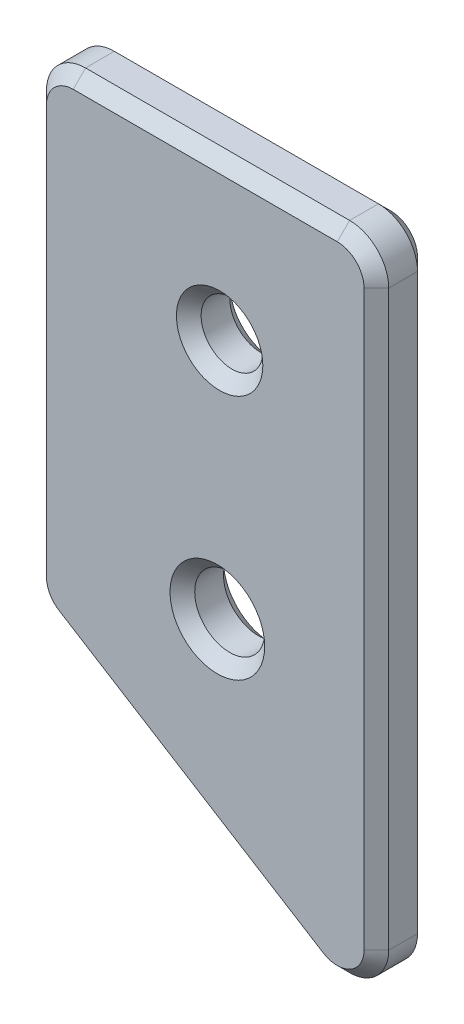
SolidWorks part; units mm, degrees
ref_plane "Front Plane" through (0, 0, 0) normal (0, 0, 1) x (1, 0, 0)
ref_plane "Top Plane" through (0, 0, 0) normal (0, 1, 0) x (1, 0, 0)
ref_plane "Right Plane" through (0, 0, 0) normal (1, 0, 0) x (0, 0, -1)
sketch "Sketch1" plane through (0, 0, 0) normal (0, 0, 1) x (1, 0, 0)
  line L3 (435.95, -297.537) -> (-11.4581, -19.05) construction
  line L9 (53.3811, -59.4088) -> (-11.4581, -19.05)
  line L11 (19.05, 19.05) -> (-13.7235, 19.05)
  line L12 (-19.05, -5.7912) -> (-19.05, 5.7912)
  line L13 (60.6412, -19.05) -> (60.6412, 14.3)
  line L14 (60.6412, -19.05) -> (60.6412, -55.3762)
  line L24 (19.05, 19.05) -> (19.05, 17.3228)
  line L25 (19.05, 17.3228) -> (704.05, 17.3228)
  line L26 (704.05, 17.3228) -> (704.05, 19.05)
  line L27 (704.05, 19.05) -> (19.05, 19.05)
  line L31 (55.8912, 19.05) -> (19.05, 19.05)
  line L44 (19.05, -6.9643) -> (19.05, -5.7912)
  line L45 (17.3228, -4.064) -> (16.7132, -4.064)
  line L46 (14.986, -5.7912) -> (14.986, -8.9963)
  line L47 (12.7826, -9.909) -> (7.8889, -5.0152)
  line L48 (6.985, -2.833) -> (6.985, 2.833)
  line L49 (7.8889, 5.0152) -> (12.7826, 9.909)
  line L50 (14.986, 8.9963) -> (14.986, 5.7912)
  line L51 (16.7132, 4.064) -> (17.3228, 4.064)
  line L52 (19.05, 5.7912) -> (19.05, 6.9643)
  line L53 (19.05, 8.9963) -> (19.05, 13.7235)
  line L54 (13.7235, 19.05) -> (8.9963, 19.05)
  line L55 (6.9643, 19.05) -> (5.7912, 19.05)
  line L56 (4.064, 17.3228) -> (4.064, 16.7132)
  line L57 (5.7912, 14.986) -> (8.9963, 14.986)
  line L58 (9.909, 12.7826) -> (5.0152, 7.8889)
  line L59 (2.833, 6.985) -> (-2.833, 6.985)
  line L60 (-5.0152, 7.8889) -> (-9.909, 12.7826)
  line L61 (-8.9963, 14.986) -> (-5.7912, 14.986)
  line L62 (-4.064, 16.7132) -> (-4.064, 17.3228)
  line L63 (-5.7912, 19.05) -> (-6.9643, 19.05)
  line L64 (-8.9963, 19.05) -> (-13.7235, 19.05)
  line L65 (-19.05, 13.7235) -> (-19.05, 8.9963)
  line L66 (-19.05, 6.9643) -> (-19.05, 5.7912)
  line L67 (-17.3228, 4.064) -> (-16.7132, 4.064)
  line L68 (-14.986, 5.7912) -> (-14.986, 8.9963)
  line L69 (-12.7826, 9.909) -> (-7.8889, 5.0152)
  line L70 (-6.985, 2.833) -> (-6.985, -2.833)
  line L71 (-7.8889, -5.0152) -> (-12.7826, -9.909)
  line L72 (-14.986, -8.9963) -> (-14.986, -5.7912)
  line L73 (-16.7132, -4.064) -> (-17.3228, -4.064)
  line L74 (-19.05, -5.7912) -> (-19.05, -6.9643)
  line L75 (-19.05, -8.9963) -> (-19.05, -13.7235)
  line L76 (-13.7235, -19.05) -> (-8.9963, -19.05)
  line L77 (-6.9643, -19.05) -> (-5.7912, -19.05)
  line L78 (-4.064, -17.3228) -> (-4.064, -16.7132)
  line L79 (-5.7912, -14.986) -> (-8.9963, -14.986)
  line L80 (-9.909, -12.7826) -> (-5.0152, -7.8889)
  line L81 (-2.833, -6.985) -> (2.833, -6.985)
  line L82 (5.0152, -7.8889) -> (9.909, -12.7826)
  line L83 (8.9963, -14.986) -> (5.7912, -14.986)
  line L84 (4.064, -16.7132) -> (4.064, -17.3228)
  line L85 (5.7912, -19.05) -> (6.9643, -19.05)
  line L86 (8.9963, -19.05) -> (13.7235, -19.05)
  line L87 (19.05, -13.7235) -> (19.05, -8.9963)
  line L108 (-8.9963, 19.05) -> (-13.7235, 19.05)
  line L109 (-19.05, 13.7235) -> (-19.05, 8.9963)
  line L110 (-19.05, 6.9643) -> (-19.05, 5.7912)
  line L118 (-19.05, -5.7912) -> (-19.05, -6.9643)
  line L119 (-19.05, -8.9963) -> (-19.05, -13.7235)
  line L120 (-13.7235, -19.05) -> (-11.4581, -19.05)
  circle A3 centre (41.315, -29.4594) radius 4.25
  circle A4 centre (41.5912, 0) radius 3.75
  arc A5 (55.8912, 19.05) -> (60.6412, 14.3) centre (55.8912, 14.3) cw
  arc A6 (60.6412, -55.3762) -> (53.3811, -59.4088) centre (55.8912, -55.3762) cw
  circle A7 centre (0, 0) radius 4.5
  arc A52 (19.05, -6.9643) -> (19.05, -8.9963) centre (19.05, -7.9803) ccw
  arc A53 (19.05, -5.7912) -> (17.3228, -4.064) centre (17.3228, -5.7912) ccw
  arc A54 (16.7132, -4.064) -> (14.986, -5.7912) centre (16.7132, -5.7912) ccw
  arc A55 (12.7826, -9.909) -> (14.986, -8.9963) centre (13.6953, -8.9963) ccw
  arc A56 (6.985, -2.833) -> (7.8889, -5.0152) centre (10.0711, -2.833) ccw
  arc A57 (7.8889, 5.0152) -> (6.985, 2.833) centre (10.0711, 2.833) ccw
  arc A58 (14.986, 8.9963) -> (12.7826, 9.909) centre (13.6953, 8.9963) ccw
  arc A59 (14.986, 5.7912) -> (16.7132, 4.064) centre (16.7132, 5.7912) ccw
  arc A60 (17.3228, 4.064) -> (19.05, 5.7912) centre (17.3228, 5.7912) ccw
  arc A61 (19.05, 8.9963) -> (19.05, 6.9643) centre (19.05, 7.9803) ccw
  arc A62 (18.8293, 15.7312) -> (19.05, 13.7235) centre (19.05, 14.7395) ccw
  arc A63 (18.8293, 15.7312) -> (15.7312, 18.8293) centre (14.3002, 14.3002) ccw
  arc A64 (13.7235, 19.05) -> (15.7312, 18.8293) centre (14.7395, 19.05) ccw
  arc A65 (6.9643, 19.05) -> (8.9963, 19.05) centre (7.9803, 19.05) ccw
  arc A66 (5.7912, 19.05) -> (4.064, 17.3228) centre (5.7912, 17.3228) ccw
  arc A67 (4.064, 16.7132) -> (5.7912, 14.986) centre (5.7912, 16.7132) ccw
  arc A68 (9.909, 12.7826) -> (8.9963, 14.986) centre (8.9963, 13.6953) ccw
  arc A69 (2.833, 6.985) -> (5.0152, 7.8889) centre (2.833, 10.0711) ccw
  arc A70 (-5.0152, 7.8889) -> (-2.833, 6.985) centre (-2.833, 10.0711) ccw
  arc A71 (-8.9963, 14.986) -> (-9.909, 12.7826) centre (-8.9963, 13.6953) ccw
  arc A72 (-5.7912, 14.986) -> (-4.064, 16.7132) centre (-5.7912, 16.7132) ccw
  arc A73 (-4.064, 17.3228) -> (-5.7912, 19.05) centre (-5.7912, 17.3228) ccw
  arc A74 (-8.9963, 19.05) -> (-6.9643, 19.05) centre (-7.9803, 19.05) ccw
  arc A75 (-15.7312, 18.8293) -> (-13.7235, 19.05) centre (-14.7395, 19.05) ccw
  arc A76 (-15.7312, 18.8293) -> (-18.8293, 15.7312) centre (-14.3002, 14.3002) ccw
  arc A77 (-19.05, 13.7235) -> (-18.8293, 15.7312) centre (-19.05, 14.7395) ccw
  arc A78 (-19.05, 6.9643) -> (-19.05, 8.9963) centre (-19.05, 7.9803) ccw
  arc A79 (-19.05, 5.7912) -> (-17.3228, 4.064) centre (-17.3228, 5.7912) ccw
  arc A80 (-16.7132, 4.064) -> (-14.986, 5.7912) centre (-16.7132, 5.7912) ccw
  arc A81 (-12.7826, 9.909) -> (-14.986, 8.9963) centre (-13.6953, 8.9963) ccw
  arc A82 (-6.985, 2.833) -> (-7.8889, 5.0152) centre (-10.0711, 2.833) ccw
  arc A83 (-7.8889, -5.0152) -> (-6.985, -2.833) centre (-10.0711, -2.833) ccw
  arc A84 (-14.986, -8.9963) -> (-12.7826, -9.909) centre (-13.6953, -8.9963) ccw
  arc A85 (-14.986, -5.7912) -> (-16.7132, -4.064) centre (-16.7132, -5.7912) ccw
  arc A86 (-17.3228, -4.064) -> (-19.05, -5.7912) centre (-17.3228, -5.7912) ccw
  arc A87 (-19.05, -8.9963) -> (-19.05, -6.9643) centre (-19.05, -7.9803) ccw
  arc A88 (-18.8293, -15.7312) -> (-19.05, -13.7235) centre (-19.05, -14.7395) ccw
  arc A89 (-18.8293, -15.7312) -> (-15.7312, -18.8293) centre (-14.3002, -14.3002) ccw
  arc A90 (-13.7235, -19.05) -> (-15.7312, -18.8293) centre (-14.7395, -19.05) ccw
  arc A91 (-6.9643, -19.05) -> (-8.9963, -19.05) centre (-7.9803, -19.05) ccw
  arc A92 (-5.7912, -19.05) -> (-4.064, -17.3228) centre (-5.7912, -17.3228) ccw
  arc A93 (-4.064, -16.7132) -> (-5.7912, -14.986) centre (-5.7912, -16.7132) ccw
  arc A94 (-9.909, -12.7826) -> (-8.9963, -14.986) centre (-8.9963, -13.6953) ccw
  arc A95 (-2.833, -6.985) -> (-5.0152, -7.8889) centre (-2.833, -10.0711) ccw
  arc A96 (5.0152, -7.8889) -> (2.833, -6.985) centre (2.833, -10.0711) ccw
  arc A97 (8.9963, -14.986) -> (9.909, -12.7826) centre (8.9963, -13.6953) ccw
  arc A98 (5.7912, -14.986) -> (4.064, -16.7132) centre (5.7912, -16.7132) ccw
  arc A99 (4.064, -17.3228) -> (5.7912, -19.05) centre (5.7912, -17.3228) ccw
  arc A100 (8.9963, -19.05) -> (6.9643, -19.05) centre (7.9803, -19.05) ccw
  arc A101 (15.7312, -18.8293) -> (13.7235, -19.05) centre (14.7395, -19.05) ccw
  arc A102 (15.7312, -18.8293) -> (18.8293, -15.7312) centre (14.3002, -14.3002) ccw
  arc A103 (19.05, -13.7235) -> (18.8293, -15.7312) centre (19.05, -14.7395) ccw
  arc A127 (-15.7312, 18.8293) -> (-13.7235, 19.05) centre (-14.7395, 19.05) ccw
  arc A128 (-15.7312, 18.8293) -> (-18.8293, 15.7312) centre (-14.3002, 14.3002) ccw
  arc A129 (-19.05, 13.7235) -> (-18.8293, 15.7312) centre (-19.05, 14.7395) ccw
  arc A130 (-19.05, 6.9643) -> (-19.05, 8.9963) centre (-19.05, 7.9803) ccw
  arc A139 (-19.05, -8.9963) -> (-19.05, -6.9643) centre (-19.05, -7.9803) ccw
  arc A140 (-18.8293, -15.7312) -> (-19.05, -13.7235) centre (-19.05, -14.7395) ccw
  arc A141 (-18.8293, -15.7312) -> (-15.7312, -18.8293) centre (-14.3002, -14.3002) ccw
  arc A142 (-13.7235, -19.05) -> (-15.7312, -18.8293) centre (-14.7395, -19.05) ccw
  dimension "D4" = 4.75
  dimension "D1" = 0
  dimension "D3" = 0
extrude "Boss-Extrude1" add sketch "Sketch1" along normal blind 6.5
sketch "Sketch2" plane through (0, 0, 0) normal (0, 0, -1) x (-1, 0, 0)
  line L44 (-19.05, -5.7912) -> (-19.05, -6.9643)
  line L45 (-16.7132, -4.064) -> (-17.3228, -4.064)
  line L46 (-14.986, -8.9963) -> (-14.986, -5.7912)
  line L47 (-7.8889, -5.0152) -> (-12.7826, -9.909)
  line L48 (-6.985, 2.833) -> (-6.985, -2.833)
  line L49 (-12.7826, 9.909) -> (-7.8889, 5.0152)
  line L50 (-14.986, 5.7912) -> (-14.986, 8.9963)
  line L51 (-17.3228, 4.064) -> (-16.7132, 4.064)
  line L52 (-19.05, 6.9643) -> (-19.05, 5.7912)
  line L53 (-19.05, 13.7235) -> (-19.05, 8.9963)
  line L54 (-8.9963, 19.05) -> (-13.7235, 19.05)
  line L55 (-5.7912, 19.05) -> (-6.9643, 19.05)
  line L56 (-4.064, 16.7132) -> (-4.064, 17.3228)
  line L57 (-8.9963, 14.986) -> (-5.7912, 14.986)
  line L58 (-5.0152, 7.8889) -> (-9.909, 12.7826)
  line L59 (2.833, 6.985) -> (-2.833, 6.985)
  line L60 (9.909, 12.7826) -> (5.0152, 7.8889)
  line L61 (5.7912, 14.986) -> (8.9963, 14.986)
  line L62 (4.064, 17.3228) -> (4.064, 16.7132)
  line L63 (6.9643, 19.05) -> (5.7912, 19.05)
  line L64 (13.7235, 19.05) -> (8.9963, 19.05)
  line L65 (19.05, 8.9963) -> (19.05, 13.7235)
  line L66 (19.05, 5.7912) -> (19.05, 6.9643)
  line L67 (16.7132, 4.064) -> (17.3228, 4.064)
  line L68 (14.986, 8.9963) -> (14.986, 5.7912)
  line L69 (7.8889, 5.0152) -> (12.7826, 9.909)
  line L70 (6.985, -2.833) -> (6.985, 2.833)
  line L71 (12.7826, -9.909) -> (7.8889, -5.0152)
  line L72 (14.986, -5.7912) -> (14.986, -8.9963)
  line L73 (17.3228, -4.064) -> (16.7132, -4.064)
  line L74 (19.05, -6.9643) -> (19.05, -5.7912)
  line L75 (19.05, -13.7235) -> (19.05, -8.9963)
  line L76 (8.9963, -19.05) -> (13.7235, -19.05)
  line L77 (5.7912, -19.05) -> (6.9643, -19.05)
  line L78 (4.064, -16.7132) -> (4.064, -17.3228)
  line L79 (8.9963, -14.986) -> (5.7912, -14.986)
  line L80 (5.0152, -7.8889) -> (9.909, -12.7826)
  line L81 (-2.833, -6.985) -> (2.833, -6.985)
  line L82 (-9.909, -12.7826) -> (-5.0152, -7.8889)
  line L83 (-5.7912, -14.986) -> (-8.9963, -14.986)
  line L84 (-4.064, -17.3228) -> (-4.064, -16.7132)
  line L85 (-6.9643, -19.05) -> (-5.7912, -19.05)
  line L86 (-13.7235, -19.05) -> (-8.9963, -19.05)
  line L87 (-19.05, -8.9963) -> (-19.05, -13.7235)
  line L88 (-19.05, -5.7912) -> (-19.05, -6.9643)
  line L89 (-16.7132, -4.064) -> (-17.3228, -4.064)
  line L90 (-14.986, -8.9963) -> (-14.986, -5.7912)
  line L91 (-7.8889, -5.0152) -> (-12.7826, -9.909)
  line L92 (-6.985, 2.833) -> (-6.985, -2.833)
  line L93 (-12.7826, 9.909) -> (-7.8889, 5.0152)
  line L94 (-14.986, 5.7912) -> (-14.986, 8.9963)
  line L95 (-17.3228, 4.064) -> (-16.7132, 4.064)
  line L96 (-19.05, 6.9643) -> (-19.05, 5.7912)
  line L97 (-19.05, 13.7235) -> (-19.05, 8.9963)
  line L98 (-8.9963, 19.05) -> (-13.7235, 19.05)
  line L99 (-5.7912, 19.05) -> (-6.9643, 19.05)
  line L100 (-4.064, 16.7132) -> (-4.064, 17.3228)
  line L101 (-8.9963, 14.986) -> (-5.7912, 14.986)
  line L102 (-5.0152, 7.8889) -> (-9.909, 12.7826)
  line L103 (2.833, 6.985) -> (-2.833, 6.985)
  line L104 (9.909, 12.7826) -> (5.0152, 7.8889)
  line L105 (5.7912, 14.986) -> (8.9963, 14.986)
  line L106 (4.064, 17.3228) -> (4.064, 16.7132)
  line L107 (6.9643, 19.05) -> (5.7912, 19.05)
  line L108 (13.7235, 19.05) -> (8.9963, 19.05)
  line L109 (19.05, 8.9963) -> (19.05, 13.7235)
  line L110 (19.05, 5.7912) -> (19.05, 6.9643)
  line L111 (16.7132, 4.064) -> (17.3228, 4.064)
  line L112 (14.986, 8.9963) -> (14.986, 5.7912)
  line L113 (7.8889, 5.0152) -> (12.7826, 9.909)
  line L114 (6.985, -2.833) -> (6.985, 2.833)
  line L115 (12.7826, -9.909) -> (7.8889, -5.0152)
  line L116 (14.986, -5.7912) -> (14.986, -8.9963)
  line L117 (17.3228, -4.064) -> (16.7132, -4.064)
  line L118 (19.05, -6.9643) -> (19.05, -5.7912)
  line L119 (19.05, -13.7235) -> (19.05, -8.9963)
  line L120 (8.9963, -19.05) -> (13.7235, -19.05)
  line L121 (5.7912, -19.05) -> (6.9643, -19.05)
  line L122 (4.064, -16.7132) -> (4.064, -17.3228)
  line L123 (8.9963, -14.986) -> (5.7912, -14.986)
  line L124 (5.0152, -7.8889) -> (9.909, -12.7826)
  line L125 (-2.833, -6.985) -> (2.833, -6.985)
  line L126 (-9.909, -12.7826) -> (-5.0152, -7.8889)
  line L127 (-5.7912, -14.986) -> (-8.9963, -14.986)
  line L128 (-4.064, -17.3228) -> (-4.064, -16.7132)
  line L129 (-6.9643, -19.05) -> (-5.7912, -19.05)
  line L130 (-13.7235, -19.05) -> (-8.9963, -19.05)
  line L131 (-19.05, -8.9963) -> (-19.05, -13.7235)
  arc A52 (-19.05, -8.9963) -> (-19.05, -6.9643) centre (-19.05, -7.9803) ccw
  arc A53 (-17.3228, -4.064) -> (-19.05, -5.7912) centre (-17.3228, -5.7912) ccw
  arc A54 (-14.986, -5.7912) -> (-16.7132, -4.064) centre (-16.7132, -5.7912) ccw
  arc A55 (-14.986, -8.9963) -> (-12.7826, -9.909) centre (-13.6953, -8.9963) ccw
  arc A56 (-7.8889, -5.0152) -> (-6.985, -2.833) centre (-10.0711, -2.833) ccw
  arc A57 (-6.985, 2.833) -> (-7.8889, 5.0152) centre (-10.0711, 2.833) ccw
  arc A58 (-12.7826, 9.909) -> (-14.986, 8.9963) centre (-13.6953, 8.9963) ccw
  arc A59 (-16.7132, 4.064) -> (-14.986, 5.7912) centre (-16.7132, 5.7912) ccw
  arc A60 (-19.05, 5.7912) -> (-17.3228, 4.064) centre (-17.3228, 5.7912) ccw
  arc A61 (-19.05, 6.9643) -> (-19.05, 8.9963) centre (-19.05, 7.9803) ccw
  arc A62 (-19.05, 13.7235) -> (-18.8293, 15.7312) centre (-19.05, 14.7395) ccw
  arc A63 (-15.7312, 18.8293) -> (-18.8293, 15.7312) centre (-14.3002, 14.3002) ccw
  arc A64 (-15.7312, 18.8293) -> (-13.7235, 19.05) centre (-14.7395, 19.05) ccw
  arc A65 (-8.9963, 19.05) -> (-6.9643, 19.05) centre (-7.9803, 19.05) ccw
  arc A66 (-4.064, 17.3228) -> (-5.7912, 19.05) centre (-5.7912, 17.3228) ccw
  arc A67 (-5.7912, 14.986) -> (-4.064, 16.7132) centre (-5.7912, 16.7132) ccw
  arc A68 (-8.9963, 14.986) -> (-9.909, 12.7826) centre (-8.9963, 13.6953) ccw
  arc A69 (-5.0152, 7.8889) -> (-2.833, 6.985) centre (-2.833, 10.0711) ccw
  arc A70 (2.833, 6.985) -> (5.0152, 7.8889) centre (2.833, 10.0711) ccw
  arc A71 (9.909, 12.7826) -> (8.9963, 14.986) centre (8.9963, 13.6953) ccw
  arc A72 (4.064, 16.7132) -> (5.7912, 14.986) centre (5.7912, 16.7132) ccw
  arc A73 (5.7912, 19.05) -> (4.064, 17.3228) centre (5.7912, 17.3228) ccw
  arc A74 (6.9643, 19.05) -> (8.9963, 19.05) centre (7.9803, 19.05) ccw
  arc A75 (13.7235, 19.05) -> (15.7312, 18.8293) centre (14.7395, 19.05) ccw
  arc A76 (18.8293, 15.7312) -> (15.7312, 18.8293) centre (14.3002, 14.3002) ccw
  arc A77 (18.8293, 15.7312) -> (19.05, 13.7235) centre (19.05, 14.7395) ccw
  arc A78 (19.05, 8.9963) -> (19.05, 6.9643) centre (19.05, 7.9803) ccw
  arc A79 (17.3228, 4.064) -> (19.05, 5.7912) centre (17.3228, 5.7912) ccw
  arc A80 (14.986, 5.7912) -> (16.7132, 4.064) centre (16.7132, 5.7912) ccw
  arc A81 (14.986, 8.9963) -> (12.7826, 9.909) centre (13.6953, 8.9963) ccw
  arc A82 (7.8889, 5.0152) -> (6.985, 2.833) centre (10.0711, 2.833) ccw
  arc A83 (6.985, -2.833) -> (7.8889, -5.0152) centre (10.0711, -2.833) ccw
  arc A84 (12.7826, -9.909) -> (14.986, -8.9963) centre (13.6953, -8.9963) ccw
  arc A85 (16.7132, -4.064) -> (14.986, -5.7912) centre (16.7132, -5.7912) ccw
  arc A86 (19.05, -5.7912) -> (17.3228, -4.064) centre (17.3228, -5.7912) ccw
  arc A87 (19.05, -6.9643) -> (19.05, -8.9963) centre (19.05, -7.9803) ccw
  arc A88 (19.05, -13.7235) -> (18.8293, -15.7312) centre (19.05, -14.7395) ccw
  arc A89 (15.7312, -18.8293) -> (18.8293, -15.7312) centre (14.3002, -14.3002) ccw
  arc A90 (15.7312, -18.8293) -> (13.7235, -19.05) centre (14.7395, -19.05) ccw
  arc A91 (8.9963, -19.05) -> (6.9643, -19.05) centre (7.9803, -19.05) ccw
  arc A92 (4.064, -17.3228) -> (5.7912, -19.05) centre (5.7912, -17.3228) ccw
  arc A93 (5.7912, -14.986) -> (4.064, -16.7132) centre (5.7912, -16.7132) ccw
  arc A94 (8.9963, -14.986) -> (9.909, -12.7826) centre (8.9963, -13.6953) ccw
  arc A95 (5.0152, -7.8889) -> (2.833, -6.985) centre (2.833, -10.0711) ccw
  arc A96 (-2.833, -6.985) -> (-5.0152, -7.8889) centre (-2.833, -10.0711) ccw
  arc A97 (-9.909, -12.7826) -> (-8.9963, -14.986) centre (-8.9963, -13.6953) ccw
  arc A98 (-4.064, -16.7132) -> (-5.7912, -14.986) centre (-5.7912, -16.7132) ccw
  arc A99 (-5.7912, -19.05) -> (-4.064, -17.3228) centre (-5.7912, -17.3228) ccw
  arc A100 (-6.9643, -19.05) -> (-8.9963, -19.05) centre (-7.9803, -19.05) ccw
  arc A101 (-13.7235, -19.05) -> (-15.7312, -18.8293) centre (-14.7395, -19.05) ccw
  arc A102 (-18.8293, -15.7312) -> (-15.7312, -18.8293) centre (-14.3002, -14.3002) ccw
  arc A103 (-18.8293, -15.7312) -> (-19.05, -13.7235) centre (-19.05, -14.7395) ccw
  arc A104 (-19.05, -8.9963) -> (-19.05, -6.9643) centre (-19.05, -7.9803) ccw
  arc A105 (-17.3228, -4.064) -> (-19.05, -5.7912) centre (-17.3228, -5.7912) ccw
  arc A106 (-14.986, -5.7912) -> (-16.7132, -4.064) centre (-16.7132, -5.7912) ccw
  arc A107 (-14.986, -8.9963) -> (-12.7826, -9.909) centre (-13.6953, -8.9963) ccw
  arc A108 (-7.8889, -5.0152) -> (-6.985, -2.833) centre (-10.0711, -2.833) ccw
  arc A109 (-6.985, 2.833) -> (-7.8889, 5.0152) centre (-10.0711, 2.833) ccw
  arc A110 (-12.7826, 9.909) -> (-14.986, 8.9963) centre (-13.6953, 8.9963) ccw
  arc A111 (-16.7132, 4.064) -> (-14.986, 5.7912) centre (-16.7132, 5.7912) ccw
  arc A112 (-19.05, 5.7912) -> (-17.3228, 4.064) centre (-17.3228, 5.7912) ccw
  arc A113 (-19.05, 6.9643) -> (-19.05, 8.9963) centre (-19.05, 7.9803) ccw
  arc A114 (-19.05, 13.7235) -> (-18.8293, 15.7312) centre (-19.05, 14.7395) ccw
  arc A115 (-15.7312, 18.8293) -> (-18.8293, 15.7312) centre (-14.3002, 14.3002) ccw
  arc A116 (-15.7312, 18.8293) -> (-13.7235, 19.05) centre (-14.7395, 19.05) ccw
  arc A117 (-8.9963, 19.05) -> (-6.9643, 19.05) centre (-7.9803, 19.05) ccw
  arc A118 (-4.064, 17.3228) -> (-5.7912, 19.05) centre (-5.7912, 17.3228) ccw
  arc A119 (-5.7912, 14.986) -> (-4.064, 16.7132) centre (-5.7912, 16.7132) ccw
  arc A120 (-8.9963, 14.986) -> (-9.909, 12.7826) centre (-8.9963, 13.6953) ccw
  arc A121 (-5.0152, 7.8889) -> (-2.833, 6.985) centre (-2.833, 10.0711) ccw
  arc A122 (2.833, 6.985) -> (5.0152, 7.8889) centre (2.833, 10.0711) ccw
  arc A123 (9.909, 12.7826) -> (8.9963, 14.986) centre (8.9963, 13.6953) ccw
  arc A124 (4.064, 16.7132) -> (5.7912, 14.986) centre (5.7912, 16.7132) ccw
  arc A125 (5.7912, 19.05) -> (4.064, 17.3228) centre (5.7912, 17.3228) ccw
  arc A126 (6.9643, 19.05) -> (8.9963, 19.05) centre (7.9803, 19.05) ccw
  arc A127 (13.7235, 19.05) -> (15.7312, 18.8293) centre (14.7395, 19.05) ccw
  arc A128 (18.8293, 15.7312) -> (15.7312, 18.8293) centre (14.3002, 14.3002) ccw
  arc A129 (18.8293, 15.7312) -> (19.05, 13.7235) centre (19.05, 14.7395) ccw
  arc A130 (19.05, 8.9963) -> (19.05, 6.9643) centre (19.05, 7.9803) ccw
  arc A131 (17.3228, 4.064) -> (19.05, 5.7912) centre (17.3228, 5.7912) ccw
  arc A132 (14.986, 5.7912) -> (16.7132, 4.064) centre (16.7132, 5.7912) ccw
  arc A133 (14.986, 8.9963) -> (12.7826, 9.909) centre (13.6953, 8.9963) ccw
  arc A134 (7.8889, 5.0152) -> (6.985, 2.833) centre (10.0711, 2.833) ccw
  arc A135 (6.985, -2.833) -> (7.8889, -5.0152) centre (10.0711, -2.833) ccw
  arc A136 (12.7826, -9.909) -> (14.986, -8.9963) centre (13.6953, -8.9963) ccw
  arc A137 (16.7132, -4.064) -> (14.986, -5.7912) centre (16.7132, -5.7912) ccw
  arc A138 (19.05, -5.7912) -> (17.3228, -4.064) centre (17.3228, -5.7912) ccw
  arc A139 (19.05, -6.9643) -> (19.05, -8.9963) centre (19.05, -7.9803) ccw
  arc A140 (19.05, -13.7235) -> (18.8293, -15.7312) centre (19.05, -14.7395) ccw
  arc A141 (15.7312, -18.8293) -> (18.8293, -15.7312) centre (14.3002, -14.3002) ccw
  arc A142 (15.7312, -18.8293) -> (13.7235, -19.05) centre (14.7395, -19.05) ccw
  arc A143 (8.9963, -19.05) -> (6.9643, -19.05) centre (7.9803, -19.05) ccw
  arc A144 (4.064, -17.3228) -> (5.7912, -19.05) centre (5.7912, -17.3228) ccw
  arc A145 (5.7912, -14.986) -> (4.064, -16.7132) centre (5.7912, -16.7132) ccw
  arc A146 (8.9963, -14.986) -> (9.909, -12.7826) centre (8.9963, -13.6953) ccw
  arc A147 (5.0152, -7.8889) -> (2.833, -6.985) centre (2.833, -10.0711) ccw
  arc A148 (-2.833, -6.985) -> (-5.0152, -7.8889) centre (-2.833, -10.0711) ccw
  arc A149 (-9.909, -12.7826) -> (-8.9963, -14.986) centre (-8.9963, -13.6953) ccw
  arc A150 (-4.064, -16.7132) -> (-5.7912, -14.986) centre (-5.7912, -16.7132) ccw
  arc A151 (-5.7912, -19.05) -> (-4.064, -17.3228) centre (-5.7912, -17.3228) ccw
  arc A152 (-6.9643, -19.05) -> (-8.9963, -19.05) centre (-7.9803, -19.05) ccw
  arc A153 (-13.7235, -19.05) -> (-15.7312, -18.8293) centre (-14.7395, -19.05) ccw
  arc A154 (-18.8293, -15.7312) -> (-15.7312, -18.8293) centre (-14.3002, -14.3002) ccw
  arc A155 (-18.8293, -15.7312) -> (-19.05, -13.7235) centre (-19.05, -14.7395) ccw
  dimension "D1" = 0
sketch "Sketch3" plane through (0, 0, 0) normal (0, 0, -1) x (-1, 0, 0)
  line L3 (19.05, 6.9643) -> (19.05, -6.9643)
  line L4 (11.4581, -19.05) -> (-19.05, -38.0396)
  line L5 (-19.05, 19.05) -> (13.7235, 19.05)
  line L7 (-19.05, 13.7235) -> (-19.05, 8.9963)
  line L8 (-19.05, 13.7235) -> (-19.05, 19.05)
  line L9 (-19.05, 8.9963) -> (-19.05, -38.0396)
  line L10 (11.4581, -19.05) -> (13.7235, -19.05)
  line L11 (13.7235, -19.05) -> (15.7312, -18.8293)
  line L12 (19.05, -6.9643) -> (19.05, -13.7235)
  line L13 (19.05, -13.7235) -> (18.8293, -15.7312)
  line L14 (19.05, 6.9643) -> (19.05, 13.7235)
  line L16 (19.05, 13.7235) -> (18.8293, 15.7312)
  line L17 (15.7312, 18.8293) -> (13.7235, 19.05)
  arc A2 (18.8293, 15.7312) -> (15.7312, 18.8293) centre (14.3002, 14.3002) ccw
  arc A3 (15.7312, -18.8293) -> (18.8293, -15.7312) centre (14.3002, -14.3002) ccw
extrude "Cut-Extrude1" cut sketch "Sketch3" against normal blind 10
fillet "Fillet1" radius 4.75 2 edges at (19.05, -38.0396, 3.25) (19.05, 19.05, 3.25)
chamfer "Chamfer1" distance 1.5 angle 45 20 edges at (45.565, -29.4594, 6.5) (45.3412, 0, 6.5) (20.4412, 17.6588, 6.5) (39.8456, 19.05, 6.5) (59.2499, 17.6588, 6.5) (60.6412, -20.5381, 6.5) (58.1976, -59.5286, 6.5) (37.3355, -49.4213, 6.5) (19.6476, -37.7077, 6.5) (19.05, -10.5506, 6.5) (45.565, -29.4594, 0) (45.3412, 0, 0) (58.1976, -59.5286, 0) (60.6412, -20.5381, 0) (59.2499, 17.6588, 0) (39.8456, 19.05, 0) (20.4412, 17.6588, 0) (19.05, -10.5506, 0) (19.6476, -37.7077, 0) (37.3355, -49.4213, 0)
